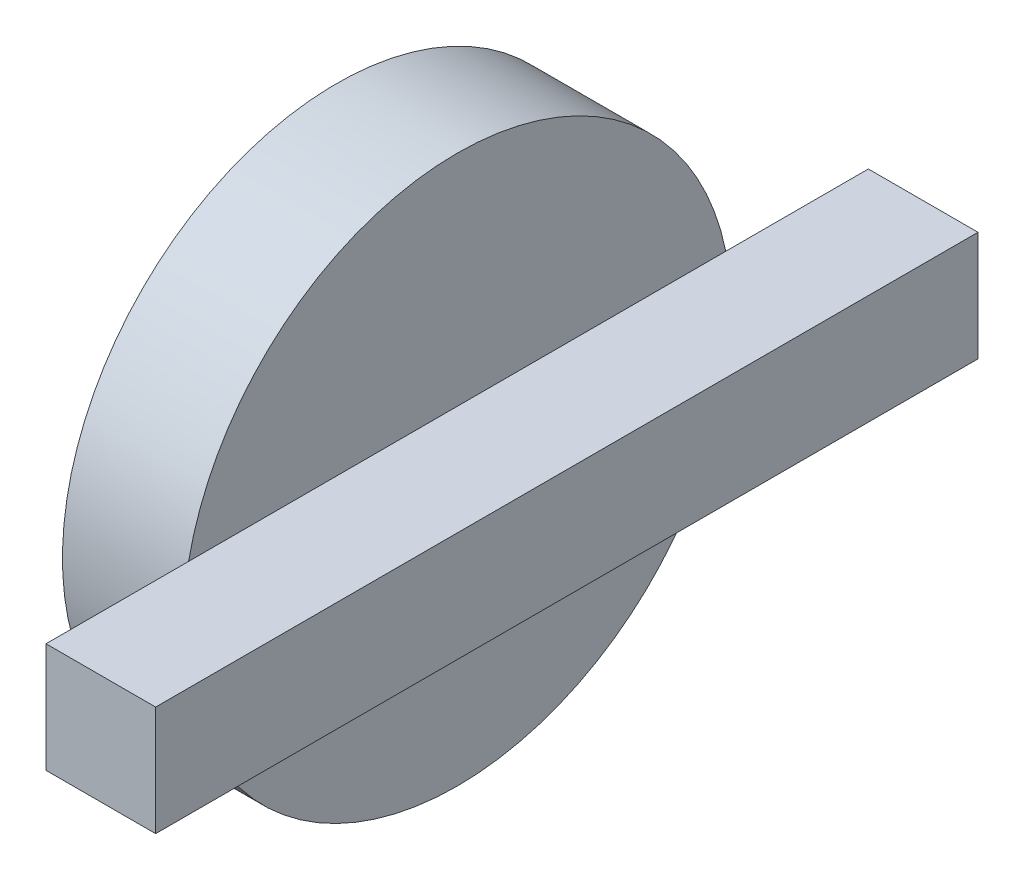
SolidWorks part; units mm, degrees
material "AISI 1020"
ref_plane "Front Plane" through (0, 0, 0) normal (0, 0, 1) x (1, 0, 0)
ref_plane "Top Plane" through (0, 0, 0) normal (0, 1, 0) x (1, 0, 0)
ref_plane "Right Plane" through (0, 0, 0) normal (1, 0, 0) x (0, 0, -1)
sketch "Sketch1" plane through (0, 0, 0) normal (1, 0, 0) x (0, 0, -1)
  circle A0 centre (0, 0) radius 50
  dimension "D1" = 100
extrude "Boss-Extrude1" add sketch "Sketch1" along normal mid plane 22
sketch "Sketch2" plane through (-11, 0, 0) normal (-1, 0, 0) x (0, 0, 1)
  circle A0 centre (0, 0) radius 30
  dimension "D1" = 60
extrude "Cut-Extrude1" cut sketch "Sketch2" against normal blind 12
sketch "Sketch3" plane through (11, 0, 0) normal (1, 0, 0) x (0, 0, -1)
  line L0 (-75, 10) -> (75, 10)
  line L1 (-75, -10) -> (75, -10)
  line L2 (0, 10) -> (0, -10) construction
  line L3 (-75, 10) -> (-75, -10)
  line L4 (75, 10) -> (75, -10)
  point P8 (0, 0)
  dimension "D1" = 20
  dimension "D2" = 150
  dimension "D3" = 150
extrude "Boss-Extrude2" add sketch "Sketch3" along normal blind 20
